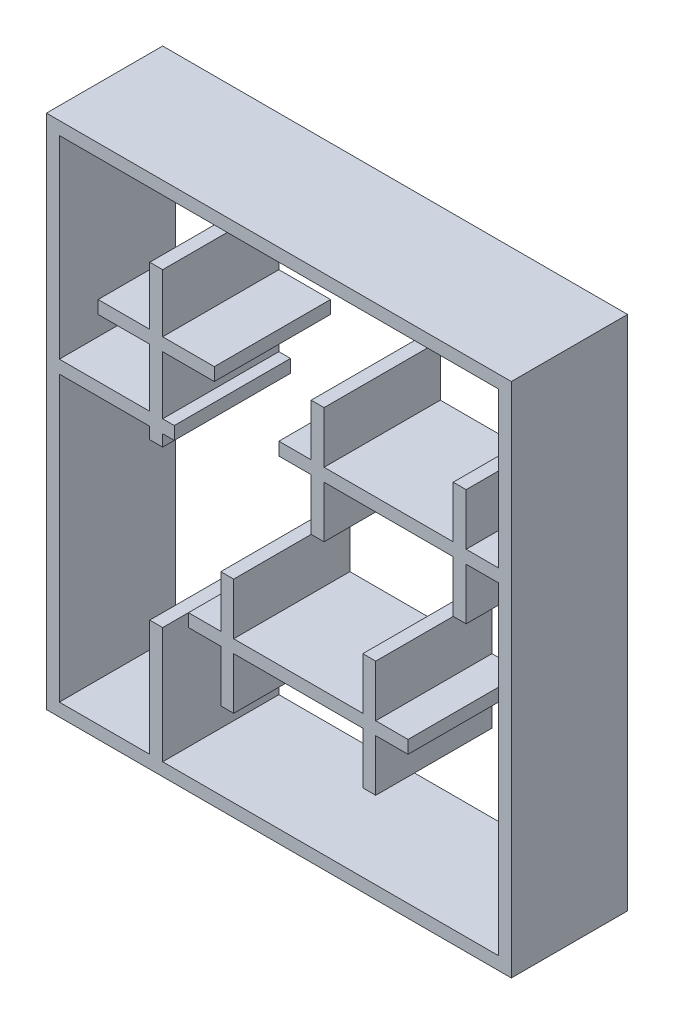
SolidWorks part; units mm, degrees
ref_plane "Front Plane" through (0, 0, 0) normal (0, 0, 1) x (1, 0, 0)
ref_plane "Top Plane" through (0, 0, 0) normal (0, 1, 0) x (1, 0, 0)
ref_plane "Right Plane" through (0, 0, 0) normal (1, 0, 0) x (0, 0, -1)
sketch "Sketch1" plane through (0, 0, 0) normal (0, 0, 1) x (1, 0, 0)
  line L0 (-85, -95) -> (-85, 95)
  line L1 (-90, -100) -> (90, -100)
  line L2 (-90, -100) -> (-90, 100)
  line L3 (-90, 100) -> (90, 100)
  line L4 (90, -100) -> (90, 100)
  line L5 (-90, -100) -> (90, 100) construction
  line L6 (-90, 100) -> (90, -100) construction
  line L7 (-85, 95) -> (85, 95)
  line L8 (85, -95) -> (85, 95)
  line L9 (-85, -95) -> (85, -95)
  line L10 (0, 32.5) -> (85, 32.5) construction
  line L15 (0, 30) -> (85, 35) construction
  line L16 (0, 35) -> (85, 30) construction
  line L21 (67.5, 10) -> (72.5, 55) construction
  line L22 (67.5, 55) -> (72.5, 10) construction
  line L27 (12.5, 10) -> (17.5, 55) construction
  line L28 (12.5, 55) -> (17.5, 10) construction
  line L29 (17.5, 55) -> (67.5, 55) construction
  line L31 (15.2778, 35) -> (17.5, 35) construction
  line L32 (14.7222, 35) -> (15.2778, 35) construction
  line L33 (12.5, 35) -> (14.7222, 35) construction
  line L34 (14.7222, 30) -> (15.2778, 30) construction
  line L35 (12.5, 30) -> (14.7222, 30) construction
  line L37 (15.2778, 30) -> (17.5, 30) construction
  line L39 (17.5, 30) -> (17.5, 31.0294) construction
  line L40 (17.5, 31.0294) -> (17.5, 32.5) construction
  line L41 (17.5, 32.5) -> (17.5, 33.9706) construction
  line L42 (17.5, 33.9706) -> (17.5, 35) construction
  line L44 (12.5, 34.2647) -> (12.5, 35) construction
  line L45 (12.5, 32.5) -> (12.5, 34.2647) construction
  line L46 (12.5, 30.7353) -> (12.5, 32.5) construction
  line L47 (12.5, 30) -> (12.5, 30.7353) construction
  line L49 (69.7222, 30) -> (70.2778, 30) construction
  line L50 (67.5, 30) -> (69.7222, 30) construction
  line L51 (70.2778, 30) -> (72.5, 30) construction
  line L53 (72.5, 30) -> (72.5, 30.7353) construction
  line L54 (72.5, 30.7353) -> (72.5, 32.5) construction
  line L55 (72.5, 32.5) -> (72.5, 34.2647) construction
  line L56 (72.5, 34.2647) -> (72.5, 35) construction
  line L58 (69.7222, 35) -> (70.2778, 35) construction
  line L59 (70.2778, 35) -> (72.5, 35) construction
  line L60 (67.5, 35) -> (69.7222, 35) construction
  line L62 (67.5, 33.9706) -> (67.5, 35) construction
  line L63 (67.5, 32.5) -> (67.5, 33.9706) construction
  line L64 (67.5, 31.0294) -> (67.5, 32.5) construction
  line L65 (67.5, 30) -> (67.5, 31.0294) construction
  line L66 (0, 30) -> (12.5, 30)
  line L67 (0, 30) -> (0, 35)
  line L68 (0, 35) -> (12.5, 35)
  line L69 (85, 30) -> (85, 35)
  line L70 (67.5, 10) -> (72.5, 10)
  line L71 (67.5, 10) -> (67.5, 30)
  line L72 (67.5, 55) -> (72.5, 55)
  line L73 (72.5, 10) -> (72.5, 30)
  line L74 (12.5, 10) -> (17.5, 10)
  line L75 (12.5, 10) -> (12.5, 30)
  line L76 (12.5, 55) -> (17.5, 55)
  line L77 (17.5, 10) -> (17.5, 30)
  line L78 (17.5, 35) -> (67.5, 35)
  line L79 (17.5, 30) -> (67.5, 30)
  line L80 (17.5, 35) -> (17.5, 55)
  line L81 (12.5, 35) -> (12.5, 55)
  line L82 (72.5, 30) -> (85, 30)
  line L83 (72.5, 35) -> (72.5, 55)
  line L84 (72.5, 35) -> (85, 35)
  line L85 (67.5, 35) -> (67.5, 55)
  line L86 (-35, -45) -> (-22.5, -45)
  line L87 (-35, -45) -> (-35, -40)
  line L88 (-35, -40) -> (-22.5, -40)
  line L89 (50, -45) -> (50, -40)
  line L90 (32.5, -65) -> (37.5, -65)
  line L91 (32.5, -65) -> (32.5, -45)
  line L92 (32.5, -20) -> (37.5, -20)
  line L93 (37.5, -65) -> (37.5, -45)
  line L94 (-22.5, -65) -> (-17.5, -65)
  line L95 (-22.5, -65) -> (-22.5, -45)
  line L96 (-22.5, -20) -> (-17.5, -20)
  line L97 (-17.5, -65) -> (-17.5, -45)
  line L98 (-17.5, -40) -> (32.5, -40)
  line L99 (-17.5, -45) -> (32.5, -45)
  line L100 (-17.5, -40) -> (-17.5, -20)
  line L101 (-22.5, -40) -> (-22.5, -20)
  line L102 (37.5, -45) -> (50, -45)
  line L103 (37.5, -40) -> (37.5, -20)
  line L104 (37.5, -40) -> (50, -40)
  line L105 (32.5, -40) -> (32.5, -20)
  line L106 (-40.5, 15) -> (-40.5, 10.5) construction
  line L107 (-50, -50) -> (-45, -50)
  line L108 (-50, -50) -> (-50, -95)
  line L109 (-50, -95) -> (-45, -95)
  line L110 (-45, -50) -> (-45, -95)
  line L111 (-85, 15) -> (-40.5, 15)
  line L112 (-85, 15) -> (-85, 20)
  line L113 (-85, 20) -> (-40.5, 20)
  line L114 (-40.5, 15) -> (-40.5, 20)
  line L115 (-45, 70) -> (-50, 70)
  line L116 (-45, 70) -> (-45, 10.5)
  line L117 (-45, 10.5) -> (-50, 10.5)
  line L118 (-50, 70) -> (-50, 10.5)
  line L119 (-40.5, 10.5) -> (-45, 10.5) construction
  line L121 (-70, 47.5) -> (-25, 47.5)
  line L122 (-70, 47.5) -> (-70, 42.5)
  line L123 (-70, 42.5) -> (-25, 42.5)
  line L124 (-25, 47.5) -> (-25, 42.5)
  point P0 (0, 0)
  point P10 (42.5, 32.5)
  point P15 (70, 32.5)
  point P20 (15, 32.5)
  point P25 (42.5, 55)
  point P108 (0, 0)
  point P114 (-47.5, 47.5)
  point P115 (-47.5, 70)
  point P116 (-51.6167, 58.8435)
  point P117 (-17.0311, 47.5)
  dimension "D1" = 180
  dimension "D2" = 200
  dimension "D4" = 35
  dimension "D5" = 5
  dimension "D6" = 85
  dimension "D7" = 60
  dimension "D8" = 45
  dimension "D9" = 50
  dimension "D10" = 50
  dimension "D11" = 5
  dimension "D12" = 85
  dimension "D13" = 45
  dimension "D14" = 50
  dimension "D15" = 35
  dimension "D16" = 45
  dimension "D17" = 5
  dimension "D18" = 4.5
  dimension "D19" = 45
  dimension "D20" = 75
  dimension "D21" = 50
  dimension "D22" = 22.5
  dimension "D23" = 35
  dimension "D3" = 5
extrude "Boss-Extrude1" add sketch "Sketch1" along normal blind 45 contours L1 L4 L3 L2 L9 L0 L7 L8 | L118 L113 L0 L111 | L123 L118 L113 L116 | L122 L123 L118 L121 | L118 L123 L116 L121 | L118 L121 L116 L115 | L124 L121 L116 L123 | L113 L118 L111 L116 | L111 L118 L117 L116 | L113 L116 L111 L114 | L85 L78 L80 L76 L81 L68 L67 L66 L75 L74 L77 L79 L71 L70 L73 L82 L8 L84 L83 L72 | L110 L107 L108 L9 | L105 L98 L100 L96 L101 L88 L87 L86 L95 L94 L97 L99 L91 L90 L93 L102 L89 L104 L103 L92
scale "Scale1" bodies to scale 101 102 scale about origin uniform scaling yes scale factor 10
